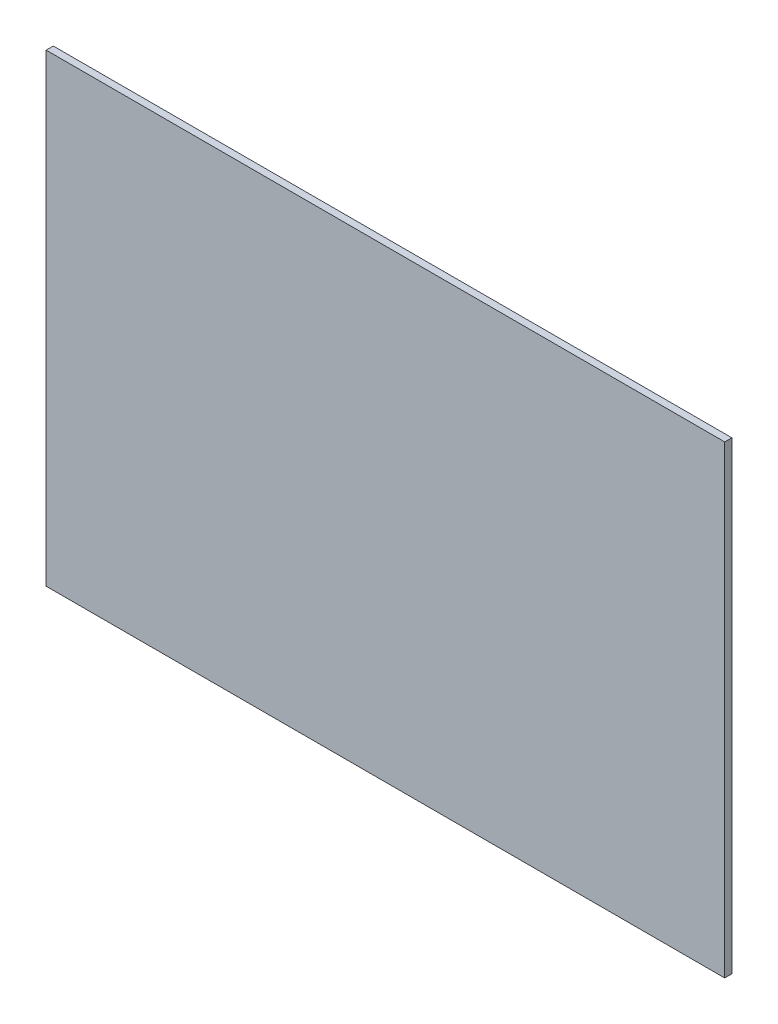
SolidWorks part; units mm, degrees
ref_plane "Plan de face" through (0, 0, 0) normal (0, 0, 1) x (1, 0, 0)
ref_plane "Plan de dessus" through (0, 0, 0) normal (0, 1, 0) x (1, 0, 0)
ref_plane "Plan de droite" through (0, 0, 0) normal (1, 0, 0) x (0, 0, -1)
sketch "Esquisse1" plane through (0, 0, 0) normal (0, 0, 1) x (1, 0, 0)
  line L1 (-47.5, 32.5) -> (47.5, 32.5)
  line L2 (-47.5, 32.5) -> (-47.5, -32.5)
  line L3 (-47.5, -32.5) -> (47.5, -32.5)
  line L4 (47.5, 32.5) -> (47.5, -32.5)
  line L5 (-47.5, 32.5) -> (47.5, -32.5) construction
  line L6 (-47.5, -32.5) -> (47.5, 32.5) construction
  point P0 (0, 0)
  dimension "D1" = 95
  dimension "D2" = 65
extrude "Boss.-Extru.1" add sketch "Esquisse1" along normal blind 1
